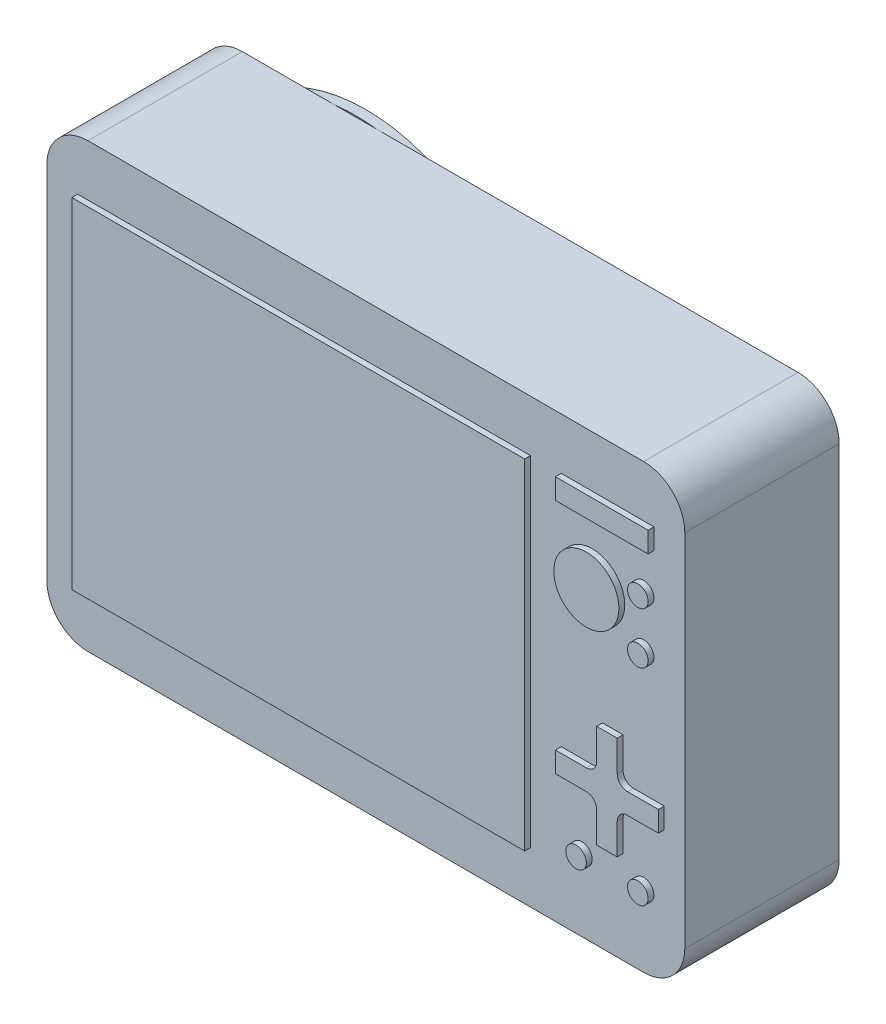
SolidWorks part; units mm, degrees
ref_plane "Front" through (0, 0, 0) normal (0, 0, 1) x (1, 0, 0)
ref_plane "Top" through (0, 0, 0) normal (0, 1, 0) x (1, 0, 0)
ref_plane "Right" through (0, 0, 0) normal (1, 0, 0) x (0, 0, -1)
sketch "Sketch1" plane through (0, 0, 0) normal (0, 0, 1) x (1, 0, 0)
  line L4 (-42.8625, 34.925) -> (42.8625, 34.925)
  line L5 (49.2125, 28.575) -> (49.2125, -26.9875)
  line L6 (42.8625, -33.3375) -> (-42.8625, -33.3375)
  line L7 (-49.2125, 28.575) -> (-49.2125, -26.9875)
  arc A4 (-49.2125, 28.575) -> (-42.8625, 34.925) centre (-42.8625, 28.575) cw
  arc A5 (49.2125, 28.575) -> (42.8625, 34.925) centre (42.8625, 28.575) ccw
  arc A6 (42.8625, -33.3375) -> (49.2125, -26.9875) centre (42.8625, -26.9875) ccw
  arc A7 (-42.8625, -33.3375) -> (-49.2125, -26.9875) centre (-42.8625, -26.9875) cw
extrude "Extrude1" add sketch "Sketch1" along normal blind 1
sketch "Sketch11" plane through (0, 0, 1) normal (0, 0, 1) x (1, 0, 0)
  line L0 (-42.8625, 34.925) -> (42.8625, 34.925)
  line L1 (-42.8625, 33.3375) -> (42.8625, 33.3375)
  line L2 (47.625, 28.575) -> (47.625, -26.9875)
  line L3 (42.8625, -31.75) -> (-42.8625, -31.75)
  line L4 (-47.625, 28.575) -> (-47.625, -26.9875)
  line L5 (-49.2125, 28.575) -> (-49.2125, -26.9875)
  line L6 (-42.8625, -33.3375) -> (42.8625, -33.3375)
  line L7 (49.2125, 28.575) -> (49.2125, -26.9875)
  arc A0 (-49.2125, 28.575) -> (-42.8625, 34.925) centre (-42.8625, 28.575) cw
  arc A1 (49.2125, 28.575) -> (42.8625, 34.925) centre (42.8625, 28.575) ccw
  arc A2 (49.2125, -26.9875) -> (42.8625, -33.3375) centre (42.8625, -26.9875) cw
  arc A3 (-42.8625, -33.3375) -> (-49.2125, -26.9875) centre (-42.8625, -26.9875) cw
  arc A4 (-42.8625, 33.3375) -> (-47.625, 28.575) centre (-42.8625, 28.575) ccw
  arc A5 (42.8625, 33.3375) -> (47.625, 28.575) centre (42.8625, 28.575) cw
  arc A6 (47.625, -26.9875) -> (42.8625, -31.75) centre (42.8625, -26.9875) cw
  arc A7 (-42.8625, -31.75) -> (-47.625, -26.9875) centre (-42.8625, -26.9875) cw
extrude "Extrude9" add sketch "Sketch11" along normal blind 21.8125
sketch "Sketch13" plane through (0, 0, 22.8125) normal (0, 0, 1) x (1, 0, 0)
  line L0 (-42.8625, 34.925) -> (42.8625, 34.925)
  line L1 (49.2125, 28.575) -> (49.2125, -26.9875)
  line L2 (42.8625, -33.3375) -> (-42.8625, -33.3375)
  line L3 (-49.2125, -26.9875) -> (-49.2125, 28.575)
  arc A0 (-49.2125, 28.575) -> (-42.8625, 34.925) centre (-42.8625, 28.575) cw
  arc A1 (42.8625, 34.925) -> (49.2125, 28.575) centre (42.8625, 28.575) cw
  arc A2 (49.2125, -26.9875) -> (42.8625, -33.3375) centre (42.8625, -26.9875) cw
  arc A3 (-49.2125, -26.9875) -> (-42.8625, -33.3375) centre (-42.8625, -26.9875) ccw
extrude "Extrude10" add sketch "Sketch13" along normal blind 1
sketch "Sketch14" plane through (0, 0, 23.8125) normal (0, 0, 1) x (1, 0, 0)
  line L0 (36.5125, -7.9375) -> (36.5125, -3.175)
  line L1 (-44.45, 26.9875) -> (25.4, 26.9875)
  line L2 (-44.45, 26.9875) -> (-44.45, -25.4)
  line L3 (-44.45, -25.4) -> (25.4, -25.4)
  line L4 (25.4, 26.9875) -> (25.4, -25.4)
  line L5 (30.1625, 26.9875) -> (44.45, 26.9875)
  line L6 (30.1625, 26.9875) -> (30.1625, 23.8125)
  line L7 (30.1625, 23.8125) -> (44.45, 23.8125)
  line L8 (44.45, 26.9875) -> (44.45, 23.8125)
  line L9 (36.5125, -3.175) -> (39.6875, -3.175)
  line L10 (39.6875, -3.175) -> (39.6875, -7.9375)
  line L11 (41.275, -9.525) -> (46.0375, -9.525)
  line L12 (46.0375, -9.525) -> (46.0375, -12.7)
  line L13 (46.0375, -12.7) -> (41.275, -12.7)
  line L14 (39.6875, -14.2875) -> (39.6875, -19.05)
  line L15 (39.6875, -19.05) -> (36.5125, -19.05)
  line L16 (36.5125, -19.05) -> (36.5125, -14.2875)
  line L17 (34.925, -12.7) -> (30.1625, -12.7)
  line L18 (30.1625, -12.7) -> (30.1625, -9.525)
  line L19 (30.1625, -9.525) -> (34.925, -9.525)
  circle A0 centre (42.8625, 17.4625) radius 1.5875
  circle A1 centre (42.8625, 9.525) radius 1.5875
  circle A2 centre (34.925, 14.2875) radius 5.0201
  circle A4 centre (33.3375, -22.225) radius 1.5875
  circle A5 centre (42.8625, -22.225) radius 1.5875
  arc A6 (39.6875, -7.9375) -> (41.275, -9.525) centre (41.275, -7.9375) ccw
  arc A7 (41.275, -12.7) -> (39.6875, -14.2875) centre (41.275, -14.2875) ccw
  arc A8 (36.5125, -14.2875) -> (34.925, -12.7) centre (34.925, -14.2875) ccw
  arc A9 (34.925, -9.525) -> (36.5125, -7.9375) centre (34.925, -7.9375) ccw
extrude "Extrude12" add sketch "Sketch14" along normal blind 0.9
sketch "Sketch15" plane through (0, 0, 0) normal (0, 0, -1) x (-1, 0, 0)
  line L0 (3.175, 30.1625) -> (-28.575, 30.1625)
  line L1 (4.7625, 28.575) -> (4.7625, 20.6375)
  line L2 (3.175, 19.05) -> (-28.575, 23.8125)
  line L3 (-30.1625, 28.575) -> (-30.1625, 25.4)
  arc A0 (3.175, 30.1625) -> (4.7625, 28.575) centre (3.175, 28.575) cw
  arc A1 (4.7625, 20.6375) -> (3.175, 19.05) centre (3.175, 20.6375) cw
  arc A2 (-28.575, 30.1625) -> (-30.1625, 28.575) centre (-28.575, 28.575) ccw
  arc A3 (-30.1625, 25.4) -> (-28.575, 23.8125) centre (-28.575, 25.4) ccw
extrude "Cut-Extrude5" cut sketch "Sketch15" against normal blind 0.2
sketch "Sketch16" plane through (0, 0, 0) normal (0, 0, -1) x (-1, 0, 0)
  arc A0 (12.7, 31.75) -> (38.1, 31.75) centre (25.4, 9.525) cw
  arc A1 (12.7, 19.05) -> (38.1, 19.05) centre (25.4, 41.275) ccw
  arc A2 (12.7, 31.75) -> (12.7, 19.05) centre (19.05, 25.4) ccw
  arc A3 (38.1, 31.75) -> (38.1, 19.05) centre (31.75, 25.4) cw
extrude "Extrude13" add sketch "Sketch16" along normal blind 1.5875
sketch "Sketch17" plane through (0, 0, -1.5875) normal (0, 0, -1) x (-1, 0, 0)
  line L1 (15.875, 31.75) -> (34.925, 31.75)
  line L2 (15.875, 31.75) -> (15.875, 19.05)
  line L3 (15.875, 19.05) -> (34.925, 19.05)
  line L4 (34.925, 31.75) -> (34.925, 19.05)
extrude "Cut-Extrude6" cut sketch "Sketch17" against normal blind 1.5
sketch "Sketch18" plane through (0, -33.3375, 0) normal (0, -1, 0) x (1, 0, 0)
  circle A0 centre (0, 11.1125) radius 4.7625
extrude "Extrude14" add sketch "Sketch18" along normal blind 0.4
sketch "Sketch19" plane through (0, -33.7375, 0) normal (0, -1, 0) x (1, 0, 0)
  circle A0 centre (0, 11.1125) radius 2.5
extrude "Cut-Extrude7" cut sketch "Sketch19" against normal blind 1
